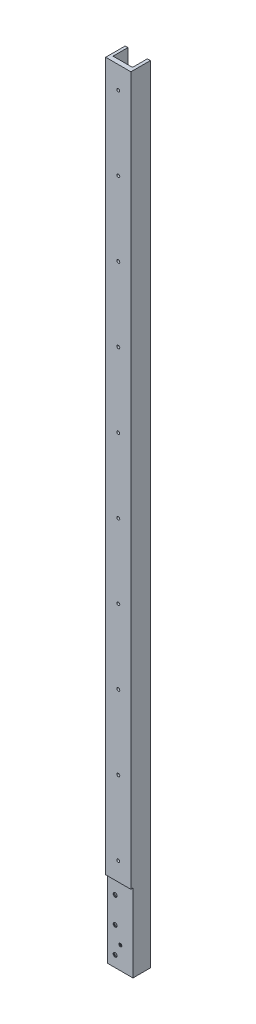
SolidWorks part; units mm, degrees
material "6061-T6 (SS)"
ref_plane "Front Plane" through (0, 0, 0) normal (0, 0, 1) x (1, 0, 0)
ref_plane "Top Plane" through (0, 0, 0) normal (0, 1, 0) x (1, 0, 0)
ref_plane "Right Plane" through (0, 0, 0) normal (1, 0, 0) x (0, 0, -1)
sketch "Sketch1" plane through (0, 0, 0) normal (0, 0, 1) x (1, 0, 0)
  line L1 (-43.18, -1221.28) -> (0, -1221.28)
  line L2 (-43.18, -1221.28) -> (-43.18, 124.92)
  line L3 (-43.18, 124.92) -> (0, 124.92)
  line L4 (0, -1221.28) -> (0, 124.92)
  dimension "D1" = 43.18
  dimension "D2" = 1346.2
extrude "Boss-Extrude1" add sketch "Sketch1" along normal blind 33.3248
sketch "Sketch9" plane through (0, 124.92, 0) normal (0, 1, 0) x (1, 0, 0)
  line L1 (-38.481, 7.7343) -> (-5.1435, 7.7343)
  line L2 (-38.481, 7.7343) -> (-38.481, -25.3873)
  line L3 (-38.481, -25.3873) -> (-5.1435, -25.3873)
  line L4 (-5.1435, 7.7343) -> (-5.1435, -25.3873)
  dimension "D1" = 7.9375
  dimension "D2" = 33.3375
  dimension "D3" = 4.699
extrude "Cut-Extrude1" cut sketch "Sketch9" against normal through all contours L3 L4 L1 L2
sketch "Sketch10" plane through (0, 0, 33.3248) normal (0, 0, 1) x (1, 0, 0)
  line L0 (-21.59, -1183.18) -> (-21.59, -1056.18) construction
  circle A0 centre (-21.59, -1183.18) radius 2.9208
  circle A1 centre (-21.59, -1056.18) radius 2.9208
  circle A2 centre (-21.59, -929.18) radius 2.9208
  circle A3 centre (-21.59, -802.18) radius 2.9208
  circle A4 centre (-21.59, -675.18) radius 2.9208
  circle A5 centre (-21.59, -548.18) radius 2.9208
  circle A6 centre (-21.59, -421.18) radius 2.9208
  circle A7 centre (-21.59, -294.18) radius 2.9208
  circle A8 centre (-21.59, -167.18) radius 2.9208
  circle A9 centre (-21.59, -40.18) radius 2.9208
  circle A10 centre (-21.59, 86.82) radius 2.9208
  dimension "D1" = 21.59
  dimension "D2" = 38.1
  dimension "D4" = 127
  dimension "D3" = 11
hole_wizard "CSK for #10 Flat Head Machine Screw3" positions "Sketch12" profile "Sketch11" countersink size "#10" standard "ANSI Inch"
sketch "Sketch12" plane through (0, 0, 25.3873) normal (0, 0, -1) x (-1, 0, 0)
  point P0 (21.59, -1183.18)
  point P3 (21.59, -1056.18)
  point P6 (21.59, -929.18)
  point P9 (21.59, -929.18)
  point P11 (21.59, -802.18)
  point P14 (21.59, -675.18)
  point P17 (21.59, -548.18)
  point P20 (21.59, -421.18)
  point P23 (21.59, -294.18)
  point P26 (21.59, -167.18)
  point P29 (21.59, -40.18)
  point P32 (21.59, 86.82)
sketch "Sketch11" plane through (-21.59, -1183.18, 25.3873) normal (1, 0, 0) x (0, 1, 0)
  line L0 (0, 0) -> (0, 77.7338)
  line L1 (0, 77.7338) -> (2.5527, 76.2)
  line L2 (2.5527, 76.2) -> (2.5527, 2.9422)
  line L3 (2.5527, 2.9422) -> (5.1103, 0)
  line L5 (5.1103, 0) -> (0, 0)
  line L6 (-2.5527, 2.9422) -> (-5.1103, 0) construction
  line L10 (0, 77.7338) -> (-2.5527, 76.2) construction
  line L11 (0, -6.35) -> (0, 107.95) construction
  dimension "Hole Dia." = 5.1054
  dimension "Hole Depth" = 76.2
  dimension "Near C'Sink Dia." = 10.2206
  dimension "Near C'Sink Angle" = 82
  dimension "Drill Angle" = 118
sketch "Sketch13" plane through (0, 0, 0) normal (1, 0, 0) x (0, 0, -1)
  line L1 (-33.3248, -1221.28) -> (-29.7688, -1221.28)
  line L2 (-33.3248, -1221.28) -> (-33.3248, -1087.93)
  line L3 (-33.3248, -1087.93) -> (-29.7688, -1087.93)
  line L4 (-29.7688, -1221.28) -> (-29.7688, -1087.93)
  dimension "D1" = 133.35
  dimension "D2" = 3.556
extrude "Cut-Extrude2" cut sketch "Sketch13" against normal through all contours L2 L3 L4 L1
hole_wizard "1/4 (0.25) Diameter Hole1" positions "Sketch14" profile "Sketch15" hole size "1/4" standard "ANSI Inch"
sketch "Sketch14" plane through (239.6063, -1806.5801, 74.9808) normal (0, 0, 1) x (1, 0, 0)
  point P0 (-270.0863, 693.2501)
  point P3 (-231.9863, 693.2501)
  point P6 (-270.0863, 648.8001)
  point P9 (-231.9863, 648.8001)
  point P12 (-270.0863, 604.3501)
  point P15 (-231.9863, 604.3501)
sketch "Sketch15" plane through (-30.48, -1113.33, 74.9808) normal (0, 1, 0) x (1, 0, 0)
  line L0 (0, 0) -> (0, 103.5077)
  line L1 (0, 103.5077) -> (3.175, 101.6)
  line L2 (3.175, 101.6) -> (3.175, 0)
  line L3 (3.175, 0) -> (0, 0)
  line L4 (0, 103.5077) -> (-3.175, 101.6) construction
  line L5 (0, -6.35) -> (0, 107.95) construction
  dimension "Hole Dia." = 6.35
  dimension "Hole Depth" = 101.6
  dimension "Drill Angle" = 118
hole_wizard "CSK for 1/4 Flat Head Machine Screw1" positions "Sketch19" profile "Sketch20" countersink size "1/4" standard "ANSI Inch" end condition through all
sketch "Sketch19" plane through (0, 0, 25.3873) normal (0, 0, -1) x (-1, 0, 0)
  point P0 (30.48, -1157.78)
  point P3 (30.48, -1202.23)
  point P6 (30.48, -1113.33)
sketch "Sketch20" plane through (-30.48, -1157.78, 25.3873) normal (1, 0, 0) x (0, 1, 0)
  line L0 (0, 0) -> (0, 7.9375)
  line L1 (0, 7.9375) -> (3.3782, 7.9375)
  line L2 (3.3782, 7.9375) -> (3.3782, 3.7749)
  line L3 (3.3782, 3.7749) -> (6.6597, 0)
  line L5 (6.6597, 0) -> (0, 0)
  line L6 (-3.3782, 3.7749) -> (-6.6597, 0) construction
  line L11 (0, -6.35) -> (0, 107.95) construction
  dimension "Thru Hole Dia." = 6.7564
  dimension "Thru Hole Depth" = 7.9375
  dimension "Near C'Sink Dia." = 13.3194
  dimension "Near C'Sink Angle" = 82
